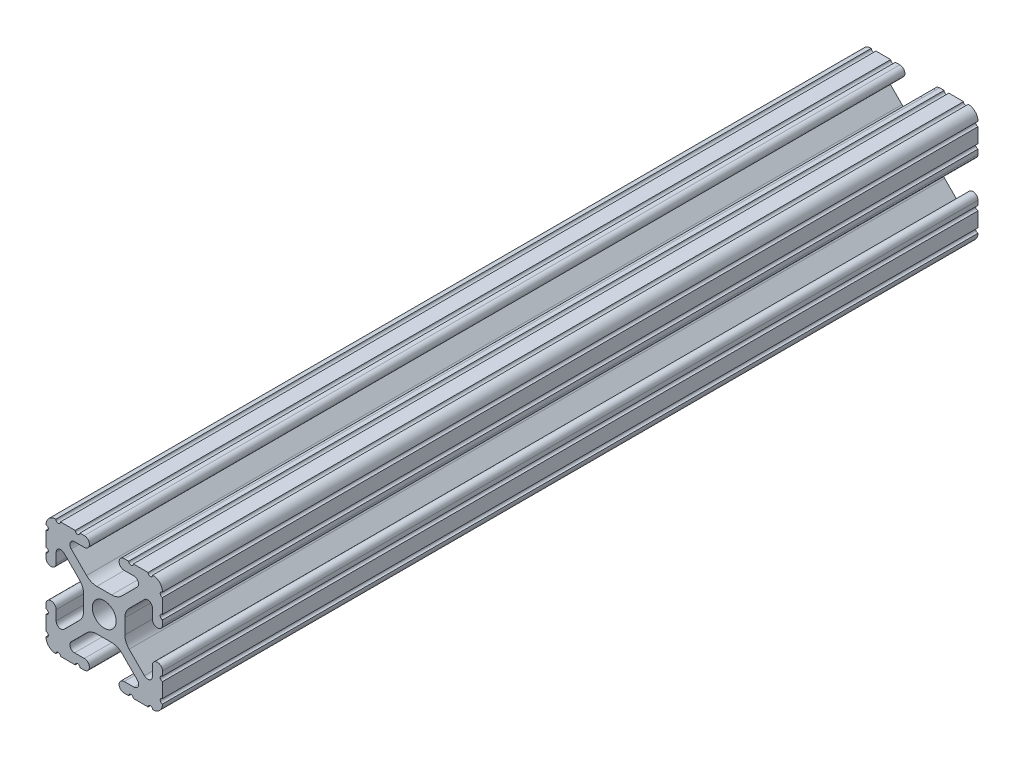
SolidWorks part; units mm, degrees
ref_plane "Front Plane" through (0, 0, 0) normal (0, 0, 1) x (1, 0, 0)
ref_plane "Top Plane" through (0, 0, 0) normal (0, 1, 0) x (1, 0, 0)
ref_plane "Right Plane" through (0, 0, 0) normal (1, 0, 0) x (0, 0, -1)
ref_plane "Plane1" through (0, 0, -25.4) normal (0, 0, -1) x (-1, 0, 0)
sketch "Sketch1" plane through (0, 0, -25.4) normal (0, 0, -1) x (-1, 0, 0)
  line L0 (12.7, -9.5504) -> (12.7, -6.3331)
  line L1 (12.7, -5.3171) -> (12.7, -4.3434)
  line L2 (10.4902, -4.3434) -> (10.4902, -6.4748)
  line L3 (8.7558, -7.1932) -> (5.4257, -3.8632)
  line L4 (4.4958, -1.6181) -> (4.4958, 1.6181)
  line L5 (5.4257, 3.8632) -> (8.7558, 7.1932)
  line L6 (10.4902, 6.4748) -> (10.4902, 4.3434)
  line L7 (12.7, 4.3434) -> (12.7, 5.3171)
  line L8 (12.7, 6.3331) -> (12.7, 9.5504)
  line L9 (9.5504, 12.7) -> (6.3331, 12.7)
  line L10 (5.3171, 12.7) -> (4.3434, 12.7)
  line L11 (4.3434, 10.4902) -> (6.4748, 10.4902)
  line L12 (7.1932, 8.7558) -> (3.8632, 5.4257)
  line L13 (1.6181, 4.4958) -> (-1.6181, 4.4958)
  line L14 (-3.8632, 5.4257) -> (-7.1932, 8.7558)
  line L15 (-6.4748, 10.4902) -> (-4.3434, 10.4902)
  line L16 (-4.3434, 12.7) -> (-5.3171, 12.7)
  line L17 (-6.3331, 12.7) -> (-9.5504, 12.7)
  line L18 (-12.7, 9.5504) -> (-12.7, 6.3331)
  line L19 (-12.7, 5.3171) -> (-12.7, 4.3434)
  line L20 (-10.4902, 4.3434) -> (-10.4902, 6.4748)
  line L21 (-8.7558, 7.1932) -> (-5.4257, 3.8632)
  line L22 (-4.4958, 1.6181) -> (-4.4958, -1.6181)
  line L23 (-5.4257, -3.8632) -> (-8.7558, -7.1932)
  line L24 (-10.4902, -6.4748) -> (-10.4902, -4.3434)
  line L25 (-12.7, -4.3434) -> (-12.7, -5.3171)
  line L26 (-12.7, -6.3331) -> (-12.7, -9.5504)
  line L27 (-9.5504, -12.7) -> (-6.3331, -12.7)
  line L28 (-5.3171, -12.7) -> (-4.3434, -12.7)
  line L29 (-4.3434, -10.4902) -> (-6.4748, -10.4902)
  line L30 (-7.1932, -8.7558) -> (-3.8632, -5.4257)
  line L31 (-1.6181, -4.4958) -> (1.6181, -4.4958)
  line L32 (3.8632, -5.4257) -> (7.1932, -8.7558)
  line L33 (6.4748, -10.4902) -> (4.3434, -10.4902)
  line L34 (4.3434, -12.7) -> (5.3171, -12.7)
  line L35 (6.3331, -12.7) -> (9.5504, -12.7)
  arc A0 (12.6998, -10.5664) -> (12.7, -9.5504) centre (12.7, -10.0584) cw
  arc A1 (12.7, -6.3331) -> (12.7, -5.3171) centre (12.7, -5.8251) cw
  arc A2 (12.7, -4.3434) -> (10.4902, -4.3434) centre (11.5951, -4.3434) ccw
  arc A3 (10.4902, -6.4748) -> (8.7558, -7.1932) centre (9.4742, -6.4748) cw
  arc A4 (5.4257, -3.8632) -> (4.4958, -1.6181) centre (7.6708, -1.6181) cw
  arc A5 (4.4958, 1.6181) -> (5.4257, 3.8632) centre (7.6708, 1.6181) cw
  arc A6 (8.7558, 7.1932) -> (10.4902, 6.4748) centre (9.4742, 6.4748) cw
  arc A7 (10.4902, 4.3434) -> (12.7, 4.3434) centre (11.5951, 4.3434) ccw
  arc A8 (12.7, 5.3171) -> (12.7, 6.3331) centre (12.7, 5.8251) cw
  arc A9 (12.7, 9.5504) -> (12.6998, 10.5664) centre (12.7, 10.0584) cw
  arc A10 (12.6998, 10.5664) -> (10.5664, 12.6998) centre (10.5918, 10.5918) ccw
  arc A11 (10.5664, 12.6998) -> (9.5504, 12.7) centre (10.0584, 12.7) cw
  arc A12 (6.3331, 12.7) -> (5.3171, 12.7) centre (5.8251, 12.7) cw
  arc A13 (4.3434, 12.7) -> (4.3434, 10.4902) centre (4.3434, 11.5951) ccw
  arc A14 (6.4748, 10.4902) -> (7.1932, 8.7558) centre (6.4748, 9.4742) cw
  arc A15 (3.8632, 5.4257) -> (1.6181, 4.4958) centre (1.6181, 7.6708) cw
  arc A16 (-1.6181, 4.4958) -> (-3.8632, 5.4257) centre (-1.6181, 7.6708) cw
  arc A17 (-7.1932, 8.7558) -> (-6.4748, 10.4902) centre (-6.4748, 9.4742) cw
  arc A18 (-4.3434, 10.4902) -> (-4.3434, 12.7) centre (-4.3434, 11.5951) ccw
  arc A19 (-5.3171, 12.7) -> (-6.3331, 12.7) centre (-5.8251, 12.7) cw
  arc A20 (-9.5504, 12.7) -> (-10.5664, 12.6998) centre (-10.0584, 12.7) cw
  arc A21 (-10.5664, 12.6998) -> (-12.6998, 10.5664) centre (-10.5918, 10.5918) ccw
  arc A22 (-12.6998, 10.5664) -> (-12.7, 9.5504) centre (-12.7, 10.0584) cw
  arc A23 (-12.7, 6.3331) -> (-12.7, 5.3171) centre (-12.7, 5.8251) cw
  arc A24 (-12.7, 4.3434) -> (-10.4902, 4.3434) centre (-11.5951, 4.3434) ccw
  arc A25 (-10.4902, 6.4748) -> (-8.7558, 7.1932) centre (-9.4742, 6.4748) cw
  arc A26 (-5.4257, 3.8632) -> (-4.4958, 1.6181) centre (-7.6708, 1.6181) cw
  arc A27 (-4.4958, -1.6181) -> (-5.4257, -3.8632) centre (-7.6708, -1.6181) cw
  arc A28 (-8.7558, -7.1932) -> (-10.4902, -6.4748) centre (-9.4742, -6.4748) cw
  arc A29 (-10.4902, -4.3434) -> (-12.7, -4.3434) centre (-11.5951, -4.3434) ccw
  arc A30 (-12.7, -5.3171) -> (-12.7, -6.3331) centre (-12.7, -5.8251) cw
  arc A31 (-12.7, -9.5504) -> (-12.6998, -10.5664) centre (-12.7, -10.0584) cw
  arc A32 (-12.6998, -10.5664) -> (-10.5664, -12.6998) centre (-10.5918, -10.5918) ccw
  arc A33 (-10.5664, -12.6998) -> (-9.5504, -12.7) centre (-10.0584, -12.7) cw
  arc A34 (-6.3331, -12.7) -> (-5.3171, -12.7) centre (-5.8251, -12.7) cw
  arc A35 (-4.3434, -12.7) -> (-4.3434, -10.4902) centre (-4.3434, -11.5951) ccw
  arc A36 (-6.4748, -10.4902) -> (-7.1932, -8.7558) centre (-6.4748, -9.4742) cw
  arc A37 (-3.8632, -5.4257) -> (-1.6181, -4.4958) centre (-1.6181, -7.6708) cw
  arc A38 (1.6181, -4.4958) -> (3.8632, -5.4257) centre (1.6181, -7.6708) cw
  arc A39 (7.1932, -8.7558) -> (6.4748, -10.4902) centre (6.4748, -9.4742) cw
  arc A40 (4.3434, -10.4902) -> (4.3434, -12.7) centre (4.3434, -11.5951) ccw
  arc A41 (5.3171, -12.7) -> (6.3331, -12.7) centre (5.8251, -12.7) cw
  arc A42 (9.5504, -12.7) -> (10.5664, -12.6998) centre (10.0584, -12.7) cw
  arc A43 (10.5664, -12.6998) -> (12.6998, -10.5664) centre (10.5918, -10.5918) ccw
  circle A44 centre (0, 0) radius 2.6035
extrude "Boss-Extrude1" add sketch "Sketch1" along normal blind 177.8
